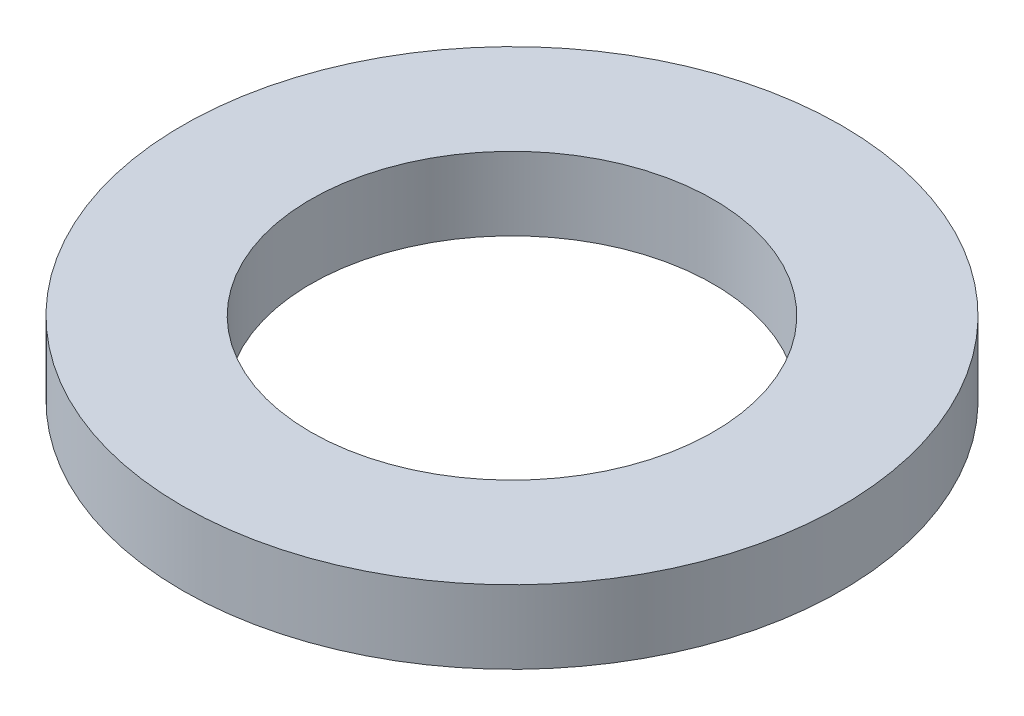
SolidWorks part; units mm, degrees
material "ASTM A36 Steel"
ref_plane "Front Plane" through (0, 0, 0) normal (0, 0, 1) x (1, 0, 0)
ref_plane "Top Plane" through (0, 0, 0) normal (0, 1, 0) x (1, 0, 0)
ref_plane "Right Plane" through (0, 0, 0) normal (1, 0, 0) x (0, 0, -1)
sketch "BodySke" plane through (0, 0, 0) normal (0, 0, -1) x (1, 0, 0)
  line L0 (0, 0) -> (0, 7.8986) construction
  line L2 (5.5, 2) -> (9, 2)
  line L3 (5.5, 2) -> (5.5, 0)
  line L4 (5.5, 0) -> (9, 0)
  line L5 (9, 2) -> (9, 0)
  dimension "Inner_dia" = 11
  dimension "Outer_dia" = 18
  dimension "Thickness" = 2
revolve "BaseBody" add sketch "BodySke" angle 360 about L0
